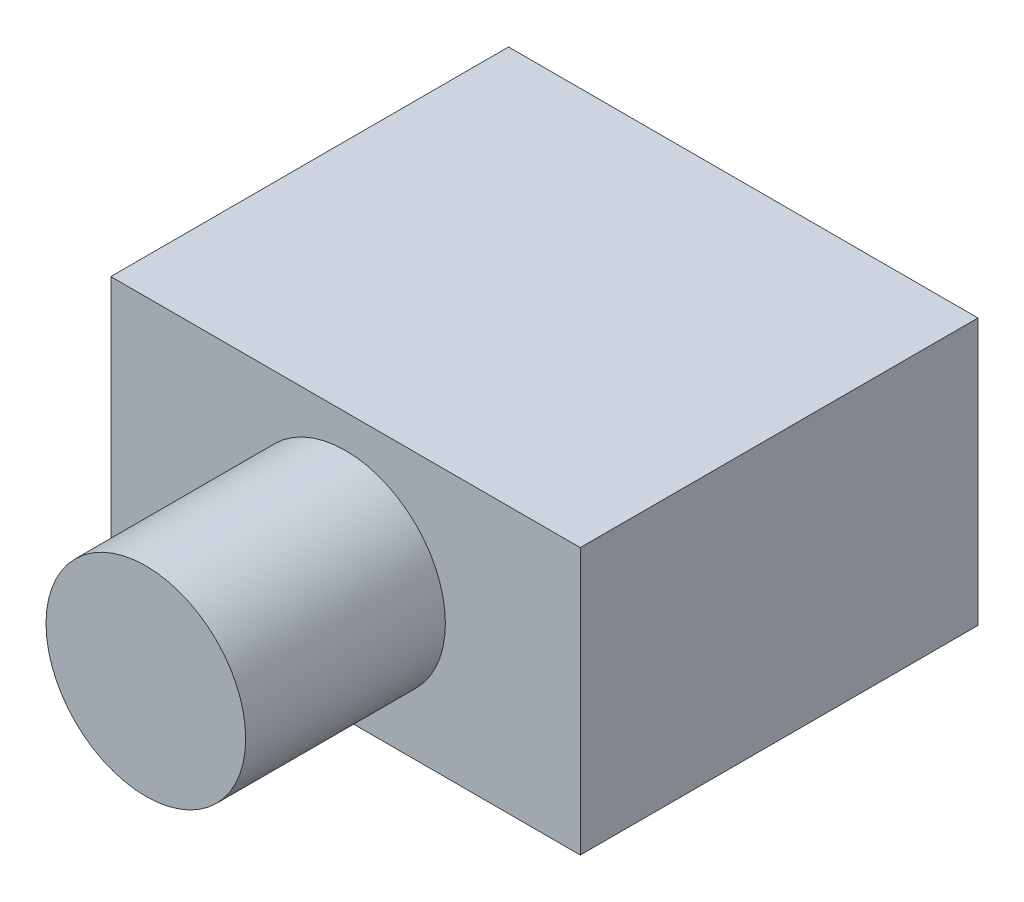
SolidWorks part; units mm, degrees
ref_plane "Plan de face" through (0, 0, 0) normal (0, 0, 1) x (1, 0, 0)
ref_plane "Plan de dessus" through (0, 0, 0) normal (0, 1, 0) x (1, 0, 0)
ref_plane "Plan de droite" through (0, 0, 0) normal (1, 0, 0) x (0, 0, -1)
sketch "Esquisse1" plane through (0, 0, 0) normal (0, 0, 1) x (1, 0, 0)
  line L1 (-14.105, -8) -> (14.105, -8)
  line L2 (-14.105, -8) -> (-14.105, 8)
  line L3 (-14.105, 8) -> (14.105, 8)
  line L4 (14.105, -8) -> (14.105, 8)
  line L5 (-14.105, -8) -> (14.105, 8) construction
  line L6 (-14.105, 8) -> (14.105, -8) construction
  point P0 (0, 0)
  dimension "D1" = 28.21
  dimension "D2" = 16
extrude "Boss.-Extru.1" add sketch "Esquisse1" along normal blind 23.9
sketch "Esquisse2" plane through (0, 0, 23.9) normal (0, 0, 1) x (1, 0, 0)
  circle A0 centre (0, 0) radius 6
  dimension "D1" = 12
extrude "Boss.-Extru.2" add sketch "Esquisse2" along normal blind 12 contours A0
